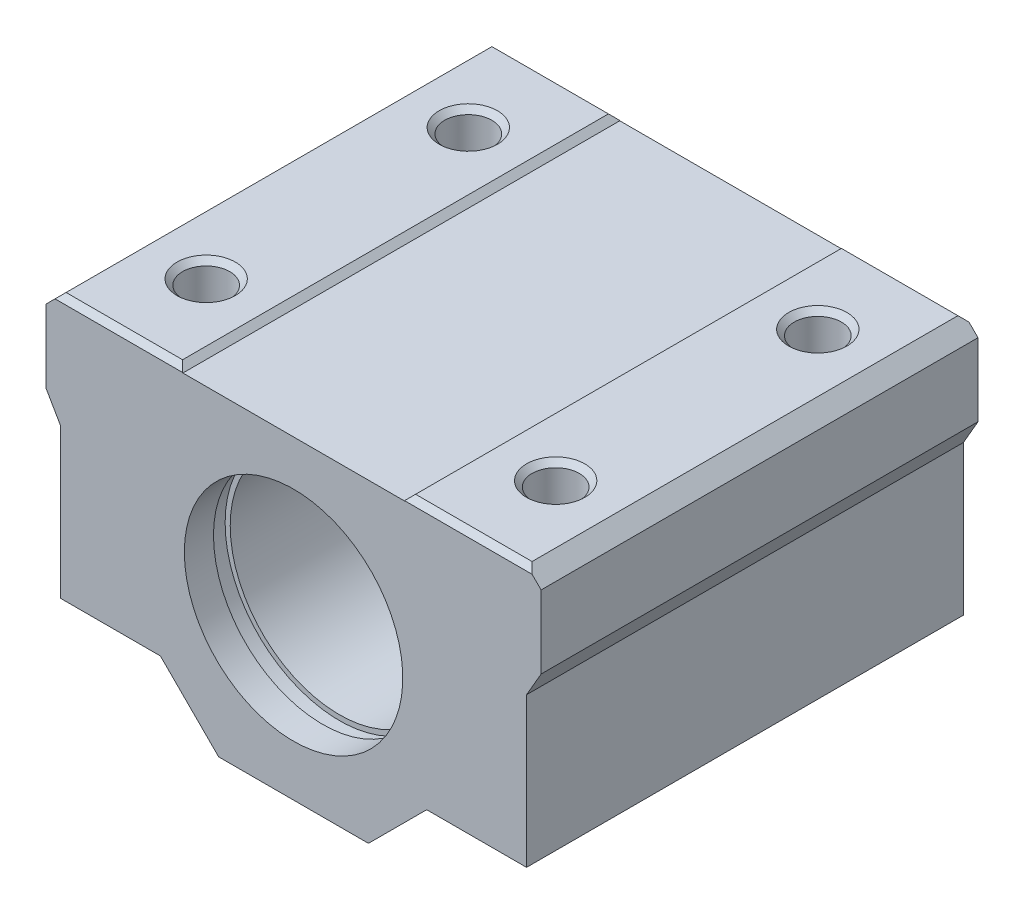
SolidWorks part; units mm, degrees
ref_plane "Piano frontale" through (0, 0, 0) normal (0, 0, 1) x (1, 0, 0)
ref_plane "Piano superiore" through (0, 0, 0) normal (0, 1, 0) x (1, 0, 0)
ref_plane "Piano destro" through (0, 0, 0) normal (1, 0, 0) x (0, 0, -1)
ref_plane "Piano1" through (0, 11, 0) normal (0, 1, 0) x (1, 0, 0)
sketch "Schizzo1" plane through (0, 11, 0) normal (0, 1, 0) x (1, 0, 0)
  line L0 (17, 0) -> (-17, 0)
  line L1 (-17, 0) -> (-17, -30)
  line L2 (-17, -30) -> (17, -30)
  line L3 (17, -30) -> (17, 0)
extrude "Estrusione-Estrusione1" add sketch "Schizzo1" against normal blind 22
sketch "Schizzo2" plane through (0, 0, 30) normal (0, 0, 1) x (1, 0, 0)
  line L0 (16, 3.2679) -> (16, -11)
  line L1 (16, -11) -> (17, -11)
  line L2 (17, -11) -> (17, 3.2679)
  line L3 (17, 3.2679) -> (16, 3.2679)
extrude "Taglio-Estrusione1" cut sketch "Schizzo2" against normal through all
sketch "Schizzo3" plane through (0, 0, 30) normal (0, 0, 1) x (1, 0, 0)
  line L0 (5.1429, -7) -> (5.1429, -11)
  line L1 (5.1429, -11) -> (16, -11)
  line L2 (16, -11) -> (16, -7)
  line L3 (16, -7) -> (5.1429, -7)
extrude "Taglio-Estrusione2" cut sketch "Schizzo3" against normal through all
sketch "Schizzo4" plane through (0, 0, 30) normal (0, 0, 1) x (1, 0, 0)
  line L0 (-5.1429, -7) -> (-17, -7)
  line L1 (-17, -7) -> (-17, -11)
  line L2 (-17, -11) -> (-5.1429, -11)
  line L3 (-5.1429, -11) -> (-5.1429, -7)
extrude "Taglio-Estrusione3" cut sketch "Schizzo4" against normal through all
sketch "Schizzo5" plane through (0, 0, 30) normal (0, 0, 1) x (1, 0, 0)
  line L0 (-16, 3.2679) -> (-17, 3.2679)
  line L1 (-17, 3.2679) -> (-17, -7)
  line L2 (-17, -7) -> (-16, -7)
  line L3 (-16, -7) -> (-16, 3.2679)
extrude "Taglio-Estrusione4" cut sketch "Schizzo5" against normal through all
sketch "Schizzo6" plane through (0, 0, 30) normal (0, 0, 1) x (1, 0, 0)
  line L0 (7.6, 11) -> (-7.6, 11)
  line L1 (-7.6, 11) -> (-7.6, 10.6)
  line L2 (-7.6, 10.6) -> (7.6, 10.6)
  line L3 (7.6, 10.6) -> (7.6, 11)
extrude "Taglio-Estrusione5" cut sketch "Schizzo6" against normal through all
draft "Sformo1" type of draft neutral plane draft angle 60 faces to draft 1 face at (16.5, 3.2679, 15) neutral plane through (16, 3.2679, 0) neutral plane normal (1, 0, 0) parameters "D1"=60
draft "Sformo2" type of draft neutral plane draft angle 60 faces to draft 1 face at (-16.5, 3.2679, 15) neutral plane through (-16, -7, 0) neutral plane normal (-1, 0, 0) parameters "D1"=60
draft "Sformo3" type of draft neutral plane draft angle 45 faces to draft 2 face at (5.1429, -9, 15) face at (-5.1429, -9, 15) neutral plane through (0, -11, 0) neutral plane normal (0, -1, 0) parameters "D1"=45
draft "Sformo4" type of draft neutral plane draft angle 45 faces to draft 2 face at (-7.6, 10.8, 15) face at (7.6, 10.8, 15) neutral plane through (-7.6, 10.6, 0) neutral plane normal (0, 1, 0) parameters "D1"=45
ref_plane "Piano2" through (0, 0, 0) normal (0, -1, 0) x (1, 0, 0)
sketch "Schizzo7" plane through (0, 0, 0) normal (0, -1, 0) x (1, 0, 0)
  line L0 (7.5, 30) -> (0, 30)
  line L1 (0, 30) -> (0, 0)
  line L2 (0, 0) -> (7.5, 0)
  line L3 (7.5, 0) -> (7.5, 2)
  line L4 (7.5, 2) -> (7.85, 2)
  line L5 (7.85, 2) -> (7.85, 3.15)
  line L6 (7.85, 3.15) -> (7.5, 3.15)
  line L7 (7.5, 3.15) -> (7.5, 26.85)
  line L8 (7.5, 26.85) -> (7.85, 26.85)
  line L9 (7.85, 26.85) -> (7.85, 28)
  line L10 (7.85, 28) -> (7.5, 28)
  line L11 (7.5, 28) -> (7.5, 30)
  line L12 (0, 30) -> (0, 0) construction
revolve "Taglia-Rivoluzione1" cut sketch "Schizzo7" angle 360 about L12
ref_plane "Piano3" through (0, 0, 6) normal (0, 0, 1) x (1, 0, 0)
sketch "Schizzo8" plane through (0, 0, 6) normal (0, 0, 1) x (1, 0, 0)
  line L0 (-10.379, 11) -> (-12, 11)
  line L1 (-12, 11) -> (-12, -7)
  line L2 (-12, -7) -> (-10.3, -7)
  line L3 (-10.3, -7) -> (-10.3, 3)
  line L4 (-10.3, 3) -> (-10.379, 3)
  line L5 (-10.379, 3) -> (-10.379, 11)
  line L6 (-12, 11) -> (-12, -7) construction
revolve "Taglia-Rivoluzione2" cut sketch "Schizzo8" angle 360 about L6
ref_plane "Piano4" through (0, 0, 24) normal (0, 0, 1) x (1, 0, 0)
sketch "Schizzo9" plane through (0, 0, 24) normal (0, 0, 1) x (1, 0, 0)
  line L0 (-10.379, 11) -> (-12, 11)
  line L1 (-12, 11) -> (-12, -7)
  line L2 (-12, -7) -> (-10.3, -7)
  line L3 (-10.3, -7) -> (-10.3, 3)
  line L4 (-10.3, 3) -> (-10.379, 3)
  line L5 (-10.379, 3) -> (-10.379, 11)
  line L6 (-12, 11) -> (-12, -7) construction
revolve "Taglia-Rivoluzione3" cut sketch "Schizzo9" angle 360 about L6
sketch "Schizzo10" plane through (0, 0, 6) normal (0, 0, 1) x (1, 0, 0)
  line L0 (13.621, 11) -> (12, 11)
  line L1 (12, 11) -> (12, -7)
  line L2 (12, -7) -> (13.7, -7)
  line L3 (13.7, -7) -> (13.7, 3)
  line L4 (13.7, 3) -> (13.621, 3)
  line L5 (13.621, 3) -> (13.621, 11)
  line L6 (12, 11) -> (12, -7) construction
revolve "Taglia-Rivoluzione4" cut sketch "Schizzo10" angle 360 about L6
sketch "Schizzo11" plane through (0, 0, 24) normal (0, 0, 1) x (1, 0, 0)
  line L0 (13.621, 11) -> (12, 11)
  line L1 (12, 11) -> (12, -7)
  line L2 (12, -7) -> (13.7, -7)
  line L3 (13.7, -7) -> (13.7, 3)
  line L4 (13.7, 3) -> (13.621, 3)
  line L5 (13.621, 3) -> (13.621, 11)
  line L6 (12, 11) -> (12, -7) construction
revolve "Taglia-Rivoluzione5" cut sketch "Schizzo11" angle 360 about L6
chamfer "Smusso1" distance 0.2309 angle 60 4 edges at (12, -7, 22.3) (12, -7, 4.3) (-12, -7, 22.3) (-12, -7, 4.3)
chamfer "Smusso2" distance 0.379 angle 45 8 edges at (12.5, 11, 0) (12, 11, 4.379) (-12.5, 11, 30) (-12, 11, 22.379) (-12, 11, 4.379) (-12.5, 11, 0) (12.5, 11, 30) (12, 11, 22.379)
chamfer "Smusso3" distance 1 angle 45 2 edges at (17, 11, 15) (-17, 11, 15)
